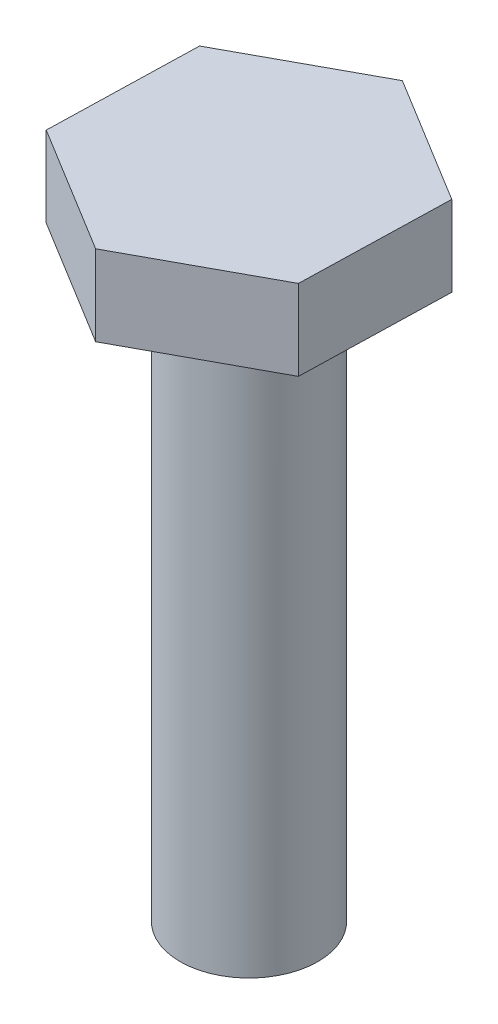
SolidWorks part; units mm, degrees
ref_plane "Front Plane" through (0, 0, 0) normal (0, 0, 1) x (1, 0, 0)
ref_plane "Top Plane" through (0, 0, 0) normal (0, 1, 0) x (1, 0, 0)
ref_plane "Right Plane" through (0, 0, 0) normal (1, 0, 0) x (0, 0, -1)
sketch "Sketch1" plane through (0, 0, 0) normal (0, 1, 0) x (1, 0, 0)
  line L1 (5.5434, -3.3943) -> (5.7112, 3.1035)
  line L2 (5.7112, 3.1035) -> (0.1679, 6.4978)
  line L3 (0.1679, 6.4978) -> (-5.5434, 3.3943)
  line L4 (-5.5434, 3.3943) -> (-5.7112, -3.1035)
  line L5 (-5.7112, -3.1035) -> (-0.1679, -6.4978)
  line L6 (-0.1679, -6.4978) -> (5.5434, -3.3943)
  circle A0 centre (0, 0) radius 5.6292 construction
extrude "Boss-Extrude1" add sketch "Sketch1" along normal blind 3.5
sketch "Sketch2" plane through (0, 0, 0) normal (0, -1, 0) x (1, 0, 0)
  circle A0 centre (0, 0) radius 3
extrude "Boss-Extrude2" add sketch "Sketch2" along normal blind 25
